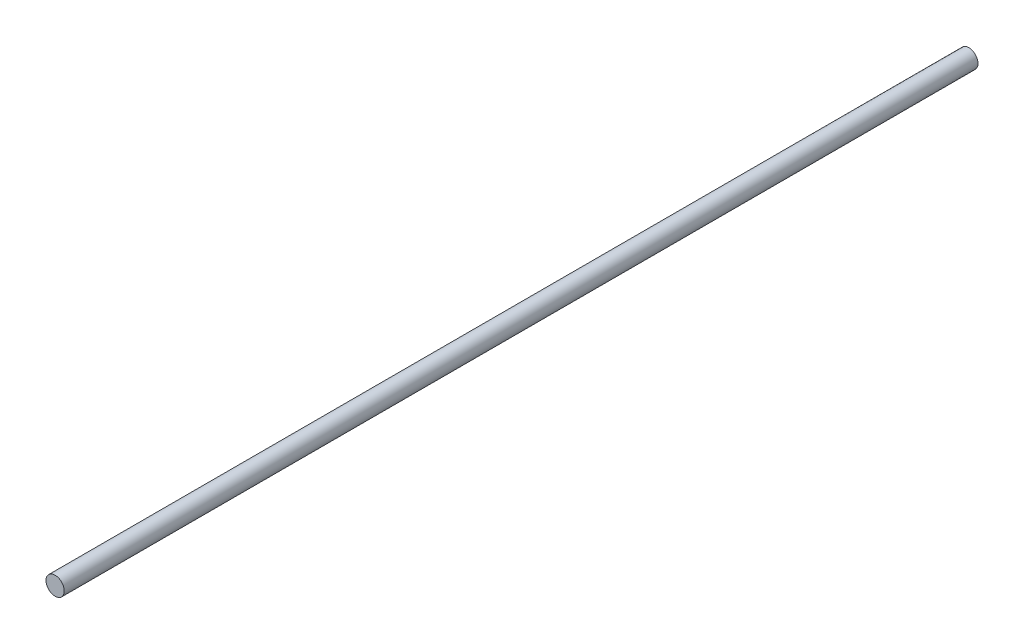
SolidWorks part; units mm, degrees
ref_plane "前视基准面" through (0, 0, 0) normal (0, 0, 1) x (1, 0, 0)
ref_plane "上视基准面" through (0, 0, 0) normal (0, 1, 0) x (1, 0, 0)
ref_plane "右视基准面" through (0, 0, 0) normal (1, 0, 0) x (0, 0, -1)
sketch "草图1" plane through (0, 0, 0) normal (0, 0, 1) x (1, 0, 0)
  circle A0 centre (0, 0) radius 1
  dimension "D1" = 2
extrude "凸台-拉伸1" add sketch "草图1" along normal blind 150
sketch "草图3" plane through (0, 0, 150) normal (0, 0, 1) x (1, 0, 0)
  circle A0 centre (0, 0) radius 1
extrude "切除-拉伸1" cut sketch "草图3" against normal blind 50
